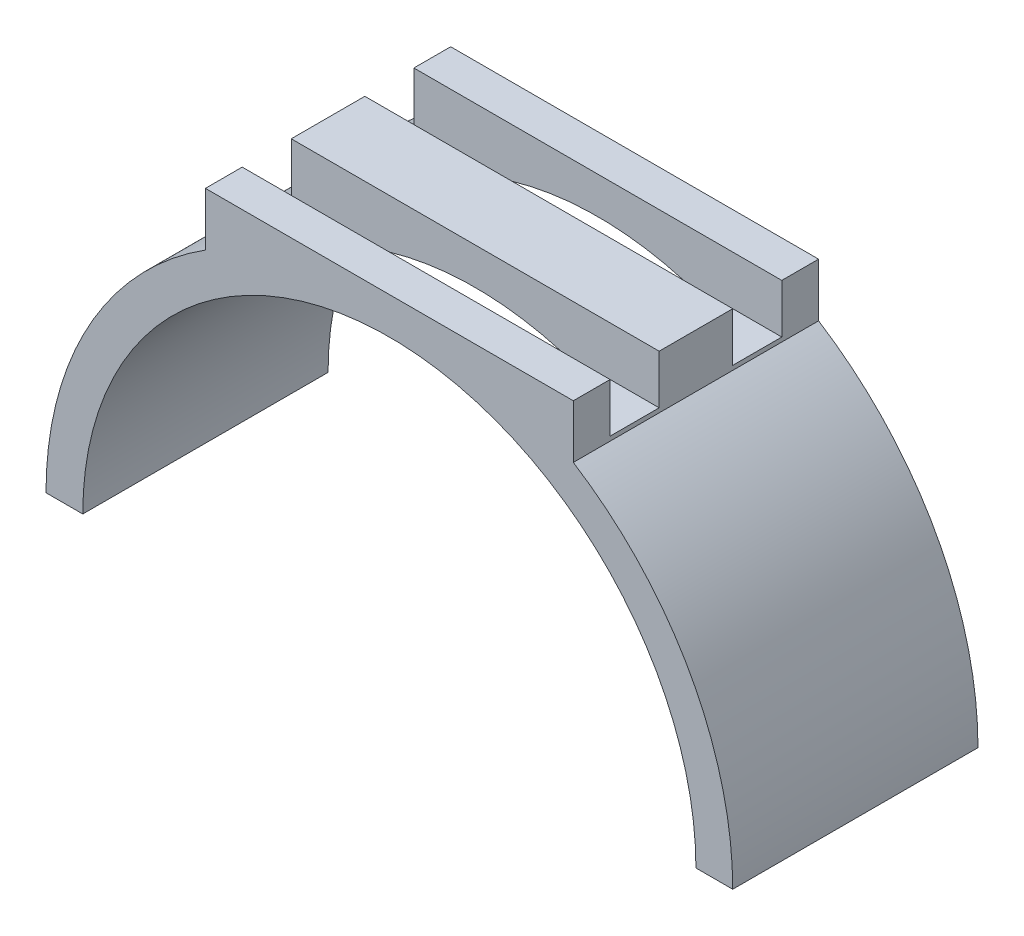
SolidWorks part; units mm, degrees
ref_plane "Alzado" through (0, 0, 0) normal (0, 0, 1) x (1, 0, 0)
ref_plane "Planta" through (0, 0, 0) normal (0, 1, 0) x (1, 0, 0)
ref_plane "Vista lateral" through (0, 0, 0) normal (1, 0, 0) x (0, 0, -1)
sketch "Croquis1" plane through (0, 0, 0) normal (0, 0, 1) x (1, 0, 0)
  line L0 (-28, 0) -> (-25, 0)
  line L1 (25, 0) -> (28, 0)
  arc A0 (25, 0) -> (-25, 0) centre (0, 0) ccw
  arc A1 (28, 0) -> (-28, 0) centre (0, 0) ccw
extrude "Saliente-Extruir1" add sketch "Croquis1" along normal blind 20
sketch "Croquis2" plane through (0, 0, 20) normal (0, 0, 1) x (1, 0, 0)
  line L0 (0, 28) -> (15, 28)
  line L1 (15, 28) -> (15, 22.5657)
  line L2 (15, 22.5657) -> (0, 26.3158)
  line L3 (0, 28) -> (-15, 28)
  line L4 (-15, 28) -> (-15, 21.9691)
  line L5 (-15, 21.9691) -> (0, 26.3158)
  arc A0 (28, 0) -> (-28, 0) centre (0, 0) ccw construction
extrude "Saliente-Extruir2" add sketch "Croquis2" against normal blind 20
sketch "Croquis3" plane through (0, 28, 0) normal (0, 1, 0) x (1, 0, 0)
  line L1 (15, 0) -> (15, -20) construction
  line L2 (15, -17) -> (-15, -17)
  line L3 (-15, 0) -> (-15, -20) construction
  line L4 (-15, -17) -> (-15, -13)
  line L5 (-15, -13) -> (15, -13)
  line L6 (15, -13) -> (15, -17)
  line L8 (15, 0) -> (15, -20) construction
  line L9 (15, -3) -> (-15, -3)
  line L10 (-15, -20) -> (-15, 0) construction
  line L11 (-15, -3) -> (-15, -7)
  line L12 (-15, -7) -> (15, -7)
  line L13 (15, -7) -> (15, -3)
extrude "Cortar-Extruir1" cut sketch "Croquis3" against normal blind 4
